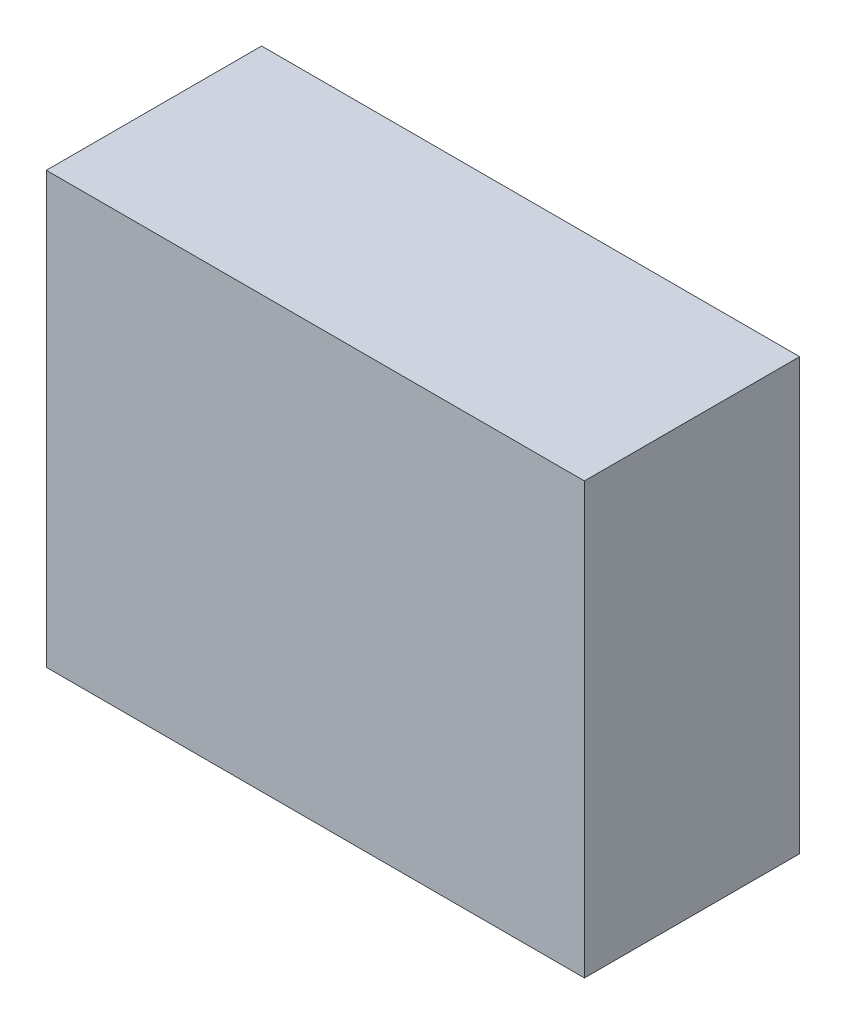
SolidWorks part; units mm, degrees
ref_plane "Front Plane" through (0, 0, 0) normal (0, 0, 1) x (1, 0, 0)
ref_plane "Top Plane" through (0, 0, 0) normal (0, 1, 0) x (1, 0, 0)
ref_plane "Right Plane" through (0, 0, 0) normal (1, 0, 0) x (0, 0, -1)
other "Configuration Table"
sketch "Sketch2" plane through (0, 0, 0) normal (0, 0, 1) x (1, 0, 0)
  line L1 (-15, -12) -> (15, -12)
  line L2 (-15, -12) -> (-15, 12)
  line L3 (-15, 12) -> (15, 12)
  line L4 (15, -12) -> (15, 12)
extrude "Reference_coupon" add sketch "Sketch2" along normal blind 12 from offset 0
